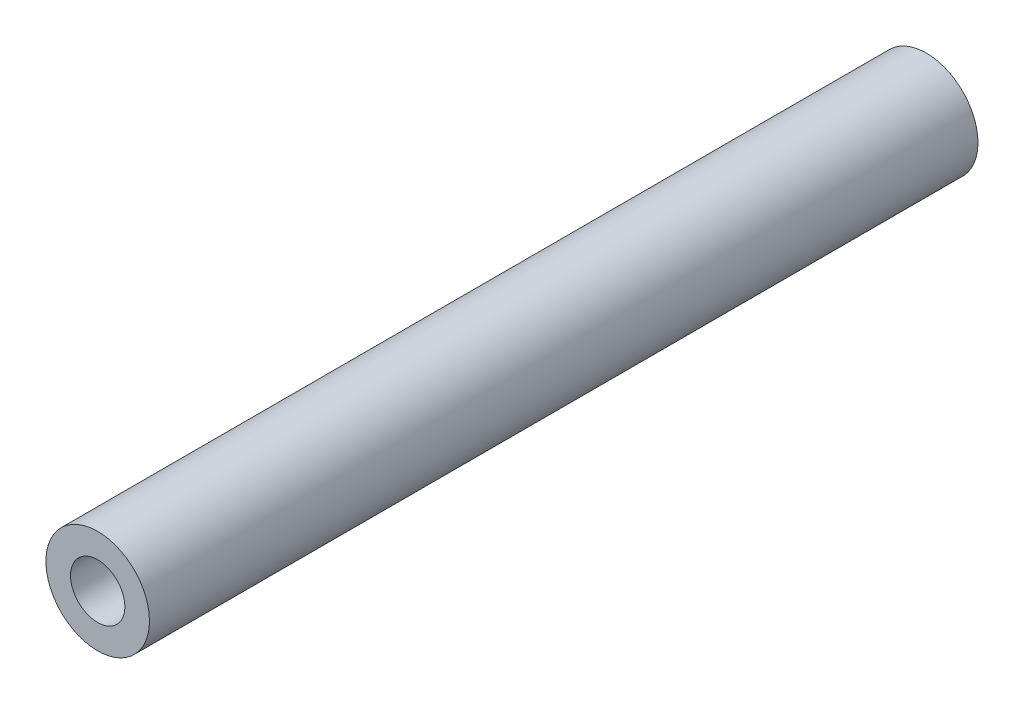
SolidWorks part; units mm, degrees
material "1023 Tôle d'acier au carbone (SS)"
ref_plane "Plan de face" through (0, 0, 0) normal (0, 0, 1) x (1, 0, 0)
ref_plane "Plan de dessus" through (0, 0, 0) normal (0, 1, 0) x (1, 0, 0)
ref_plane "Plan de droite" through (0, 0, 0) normal (1, 0, 0) x (0, 0, -1)
sketch "Esquisse1" plane through (0, 0, 0) normal (0, 0, 1) x (1, 0, 0)
  circle A0 centre (0, 0) radius 2.1
  circle A1 centre (0, 0) radius 4
  dimension "D1" = 4.2
  dimension "D2" = 8
extrude "Boss.-Extru.1" add sketch "Esquisse1" along normal blind 64
